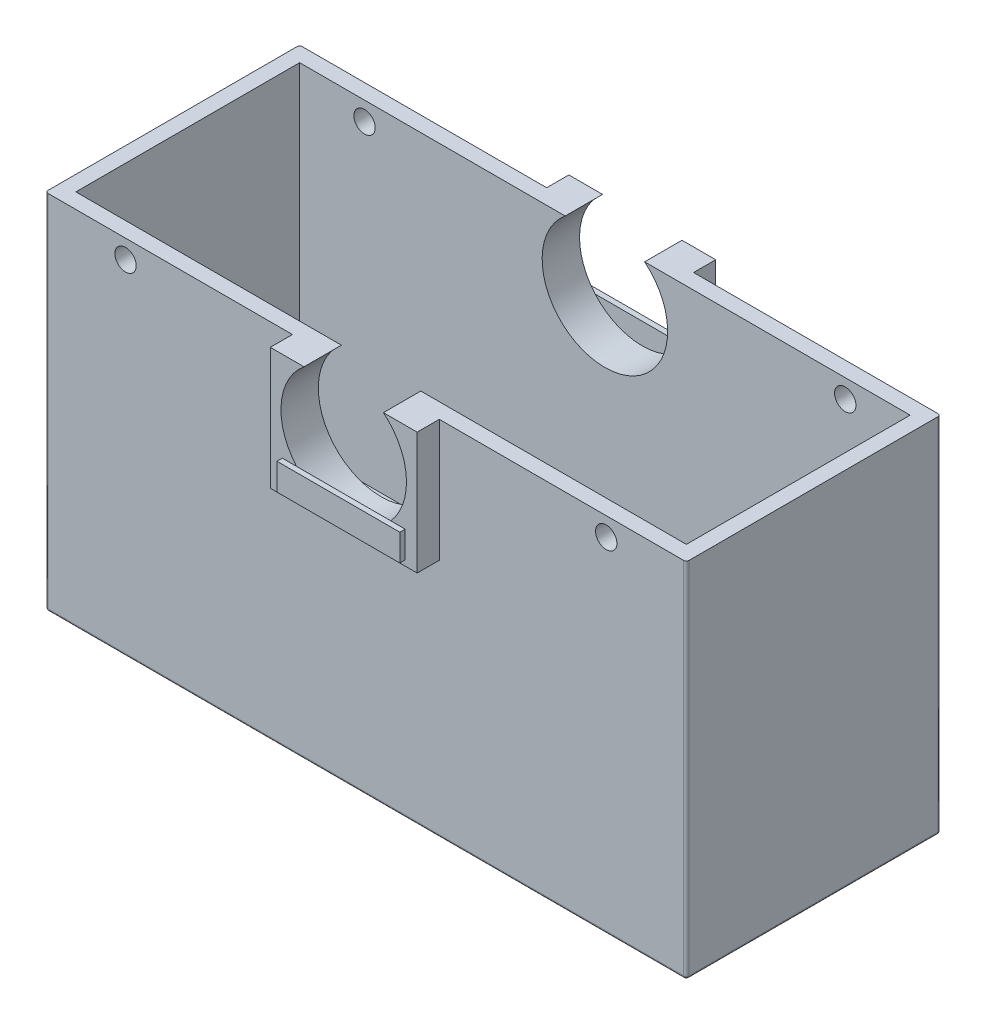
SolidWorks part; units mm, degrees
ref_plane "Front Plane" through (0, 0, 0) normal (0, 0, 1) x (1, 0, 0)
ref_plane "Top Plane" through (0, 0, 0) normal (0, 1, 0) x (1, 0, 0)
ref_plane "Right Plane" through (0, 0, 0) normal (1, 0, 0) x (0, 0, -1)
sketch "Sketch1" plane through (0, 0, 0) normal (1, 0, 0) x (0, 0, -1)
  line L1 (0, 0) -> (95.2, 0)
  line L2 (0, 0) -> (0, 135.7)
  line L3 (0, 135.7) -> (95.2, 135.7)
  line L4 (95.2, 0) -> (95.2, 135.7)
  dimension "D1" = 135.7
  dimension "130.7" = 95.2
extrude "Boss-Extrude1" add sketch "Sketch1" against normal blind 240
sketch "Sketch3" plane through (0, 135.7, 0) normal (0, 1, 0) x (1, 0, 0)
  line L0 (0, 95.2) -> (0, 0) construction
  line L1 (-234.3, 89.5) -> (-5.7, 89.5)
  line L2 (-234.3, 89.5) -> (-234.3, 5.7)
  line L3 (-234.3, 5.7) -> (-5.7, 5.7)
  line L4 (-5.7, 89.5) -> (-5.7, 5.7)
  line L5 (-240, 0) -> (0, 0) construction
  line L6 (-240, 95.2) -> (-240, 0) construction
  line L7 (-240, 95.2) -> (0, 95.2) construction
  dimension "D1" = 5.7
  dimension "D2" = 5.7
  dimension "D3" = 5.7
  dimension "D4" = 5.7
extrude "Cut-Extrude1" cut sketch "Sketch3" against normal blind 124.3
fillet "Fillet1" radius 1 8 edges at (-120, 0, 0) (-240, 67.85, 0) (-240, 0, -47.6) (-240, 67.85, -95.2) (-120, 0, -95.2) (0, 0, -47.6) (0, 67.85, -95.2) (0, 67.85, 0)
sketch "Sketch6" plane through (0, 0, 0) normal (0, 0, 1) x (1, 0, 0)
  line L0 (0, 135.7) -> (0, 1) construction
  line L1 (-1, 0) -> (-239, 0) construction
  circle A0 centre (-120, 117.5) radius 23.5
  dimension "D1" = 120
  dimension "D2" = 117.5
  dimension "D3" = 47
extrude "Cut-Extrude2" cut sketch "Sketch6" against normal blind 140 contours A0
sketch "Sketch7" plane through (0, 0, 0) normal (0, 0, 1) x (1, 0, 0)
  line L0 (-239, 135.7) -> (-134.8664, 135.7) construction
  line L1 (-147.5, 135.7) -> (-92.5, 135.7)
  line L2 (-147.5, 135.7) -> (-147.5, 90)
  line L3 (-147.5, 90) -> (-92.5, 90)
  line L4 (-92.5, 135.7) -> (-92.5, 90)
  arc A1 (-134.8664, 135.7) -> (-105.1336, 135.7) centre (-120, 117.5) ccw construction
  dimension "D1" = 55
  dimension "D2" = 27.5
  dimension "D3" = 27.5
extrude "Boss-Extrude2" add sketch "Sketch7" along normal blind 8.3
sketch "Sketch8" plane through (0, 0, -95.2) normal (0, 0, -1) x (-1, 0, 0)
  circle A0 centre (120, 117.5) radius 23.5
  dimension "D1" = 47
extrude "Cut-Extrude3" cut sketch "Sketch8" against normal through all
sketch "Sketch9" plane through (0, 0, -95.2) normal (0, 0, -1) x (-1, 0, 0)
  line L0 (105.1336, 135.7) -> (1, 135.7) construction
  line L1 (92.5, 135.7) -> (147.5, 135.7)
  line L2 (92.5, 135.7) -> (92.5, 90)
  line L3 (92.5, 90) -> (147.5, 90)
  line L4 (147.5, 135.7) -> (147.5, 90)
  arc A0 (105.1336, 135.7) -> (134.8664, 135.7) centre (120, 117.5) ccw construction
  dimension "D3" = 27.5
  dimension "D1" = 55
  dimension "D2" = 27.5
extrude "Boss-Extrude3" add sketch "Sketch9" along normal blind 8.3 contours L3 L4 L1 L2
sketch "Sketch10" plane through (0, 0, 8.3) normal (0, 0, 1) x (1, 0, 0)
  line L0 (-92.5, 135.7) -> (-105.1336, 135.7) construction
  circle A0 centre (-120, 117.5) radius 23.5
  dimension "D1" = 47
extrude "Cut-Extrude4" cut sketch "Sketch10" against normal through all
sketch "Sketch11" plane through (0, 0, 0) normal (0, 0, 1) x (1, 0, 0)
  line L0 (0, 135.7) -> (0, 1) construction
  line L1 (-92.5, 135.7) -> (-1, 135.7) construction
  circle A0 centre (-30, 128.7) radius 4
  circle A1 centre (-210, 128.7) radius 4
  dimension "D1" = 8
  dimension "D2" = 8
  dimension "D5" = 7
  dimension "D3" = 180
  dimension "D4" = 30
extrude "Cut-Extrude5" cut sketch "Sketch11" against normal through all both
sketch "Sketch12" plane through (0, 0, 8.3) normal (0, 0, 1) x (1, 0, 0)
  line L0 (-147.5, 90) -> (-92.5, 90) construction
  line L1 (-143, 92) -> (-97, 92)
  line L2 (-143, 92) -> (-143, 102)
  line L3 (-143, 102) -> (-97, 102)
  line L4 (-97, 92) -> (-97, 102)
  arc A0 (-134.8664, 135.7) -> (-105.1336, 135.7) centre (-120, 117.5) ccw construction
  dimension "D1" = 46
  dimension "D2" = 23
  dimension "D3" = 2
  dimension "D4" = 10
extrude "Boss-Extrude4" add sketch "Sketch12" along normal blind 2
sketch "Sketch13" plane through (0, 0, -103.5) normal (0, 0, -1) x (-1, 0, 0)
  line L0 (92.5, 90) -> (147.5, 90) construction
  line L1 (97, 92) -> (143, 92)
  line L2 (97, 92) -> (97, 102)
  line L3 (97, 102) -> (143, 102)
  line L4 (143, 92) -> (143, 102)
  arc A0 (105.1336, 135.7) -> (134.8664, 135.7) centre (120, 117.5) ccw construction
  dimension "D1" = 46
  dimension "D2" = 23
  dimension "D3" = 2
  dimension "D4" = 10
extrude "Boss-Extrude5" add sketch "Sketch13" along normal blind 2
